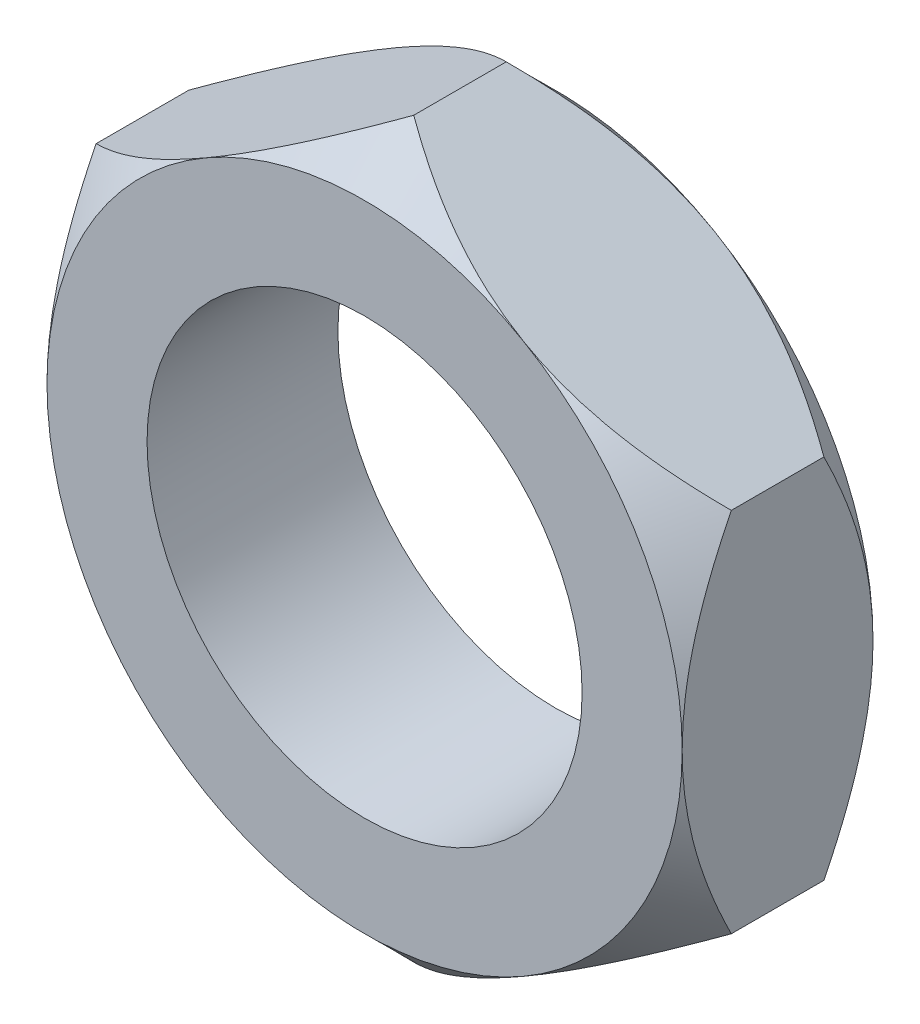
SolidWorks part; units mm, degrees
ref_plane "Front Plane" through (0, 0, 0) normal (0, 0, 1) x (1, 0, 0)
ref_plane "Top Plane" through (0, 0, 0) normal (0, 1, 0) x (1, 0, 0)
ref_plane "Right Plane" through (0, 0, 0) normal (1, 0, 0) x (0, 0, -1)
sketch "Sketch1" plane through (0, 0, 0) normal (0, 0, 1) x (1, 0, 0)
  line L1 (0, 12.644) -> (-10.95, 6.322)
  line L2 (-10.95, 6.322) -> (-10.95, -6.322)
  line L3 (-10.95, -6.322) -> (0, -12.644)
  line L4 (0, -12.644) -> (10.95, -6.322)
  line L5 (10.95, -6.322) -> (10.95, 6.322)
  line L6 (10.95, 6.322) -> (0, 12.644)
  circle A0 centre (0, 0) radius 10.95 construction
  circle A1 centre (0, 0) radius 7.5
  dimension "D2" = 15
  dimension "D1" = 21.9
extrude "Boss-Extrude1" add sketch "Sketch1" along normal blind 6.58
sketch "Sketch2" plane through (0, 0, 6.58) normal (0, 0, 1) x (1, 0, 0)
  circle A0 centre (0, 0) radius 10.95
extrude "Cut-Extrude1" cut sketch "Sketch2" against normal blind 6.58 draft 45 flip side to cut
ref_plane "Plane1" through (0, 0, 3.29) normal (0, 0, 1) x (1, 0, 0)
mirror "Mirror1" about plane through (0, 0, 3.29) normal (0, 0, 1) of "Cut-Extrude1"
sketch "Sketch3" plane through (0, 0, 0) normal (0, 0, -1) x (-1, 0, 0)
  line L0 (-5.7554, 0) -> (6.4194, 0)
